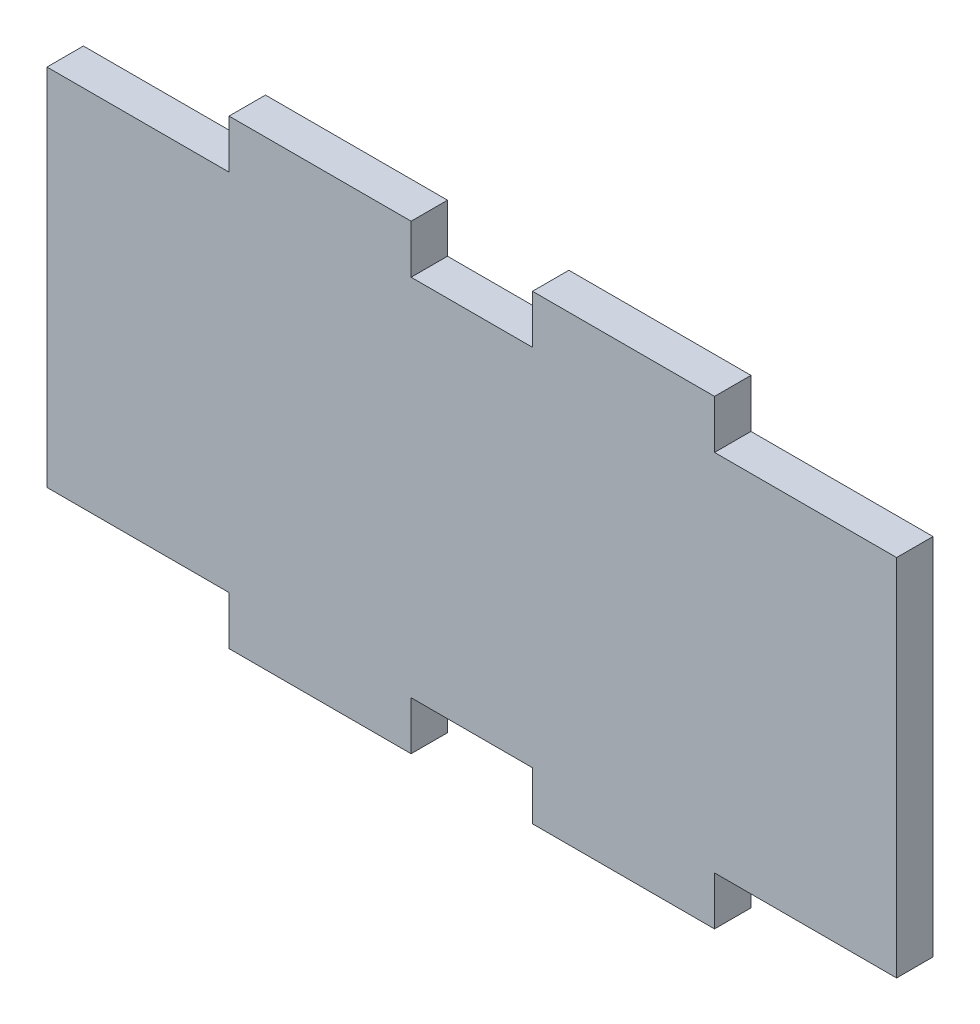
SolidWorks part; units mm, degrees
ref_plane "Front Plane" through (0, 0, 0) normal (0, 0, 1) x (1, 0, 0)
ref_plane "Top Plane" through (0, 0, 0) normal (0, 1, 0) x (1, 0, 0)
ref_plane "Right Plane" through (0, 0, 0) normal (1, 0, 0) x (0, 0, -1)
sketch "Sketch1" plane through (0, 0, 0) normal (0, 0, 1) x (1, 0, 0)
  line L1 (0, 0) -> (-70, 0)
  line L2 (0, 0) -> (0, 30)
  line L3 (0, 30) -> (-70, 30)
  line L4 (-70, 0) -> (-70, 30)
  dimension "D1" = 70
  dimension "D2" = 30
extrude "Boss-Extrude1" add sketch "Sketch1" along normal blind 3
sketch "Sketch2" plane through (0, 0, 3) normal (0, 0, 1) x (1, 0, 0)
  line L2 (0, 34) -> (-70, 34)
  line L3 (-15, 34) -> (-30, 34)
  line L4 (-55, 30) -> (-40, 30)
  line L6 (-55, 34) -> (-55, 30)
  line L7 (-15, 34) -> (-15, 30)
  line L8 (-40, 34) -> (-40, 30)
  line L9 (-30, 34) -> (-30, 30)
  line L10 (-40, 34) -> (-55, 34)
  line L11 (-30, 30) -> (-15, 30)
  line L12 (-70, 15) -> (0, 15) construction
  line L13 (-70, 30) -> (-70, 0) construction
  line L14 (0, 0) -> (0, 30) construction
  line L15 (-30, 0) -> (-15, 0)
  line L16 (-40, -4) -> (-55, -4)
  line L17 (-30, -4) -> (-30, 0)
  line L18 (-40, -4) -> (-40, 0)
  line L19 (-15, -4) -> (-15, 0)
  line L20 (-55, -4) -> (-55, 0)
  line L21 (-55, 0) -> (-40, 0)
  line L22 (-15, -4) -> (-30, -4)
  dimension "D4" = 15
  dimension "D5" = 15
  dimension "D1" = 4
extrude "Boss-Extrude2" add sketch "Sketch2" against normal blind 3
